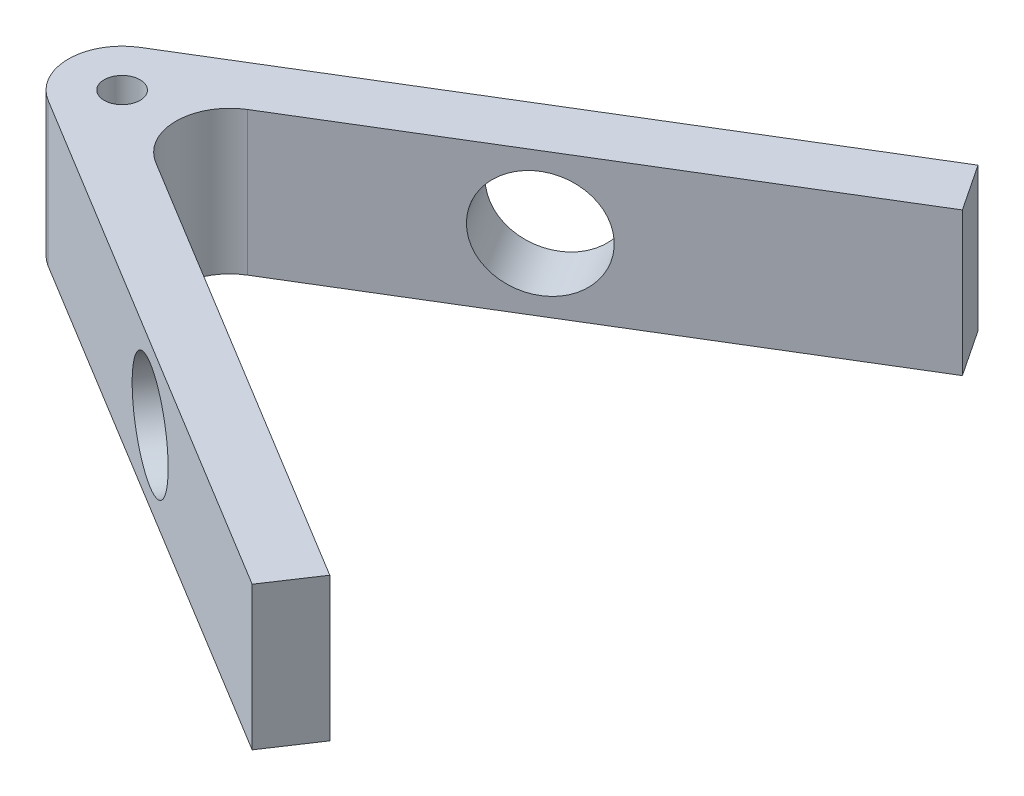
SolidWorks part; units mm, degrees
ref_plane "Front Plane" through (0, 0, 0) normal (0, 0, 1) x (1, 0, 0)
ref_plane "Top Plane" through (0, 0, 0) normal (0, 1, 0) x (1, 0, 0)
ref_plane "Right Plane" through (0, 0, 0) normal (1, 0, 0) x (0, 0, -1)
sketch "Sketch1" plane through (0, 0, 0) normal (0, 1, 0) x (1, 0, 0)
  line L0 (-47.5638, 0) -> (71.5683, 0) construction
  line L1 (-37.328, 12.8145) -> (107.9032, 101.1768)
  line L2 (-7.328, 12.8145) -> (116.5457, 88.1824)
  line L3 (116.5457, 88.1824) -> (107.9032, 101.1768)
  line L4 (116.5457, -88.1824) -> (107.9032, -101.1768)
  line L5 (-7.328, -12.8145) -> (116.5457, -88.1824)
  line L6 (-37.328, -12.8145) -> (107.9032, -101.1768)
  circle A0 centre (-29.5313, 0) radius 5
  arc A1 (-37.328, 12.8145) -> (-37.328, -12.8145) centre (-29.5313, 0) ccw
  arc A2 (-7.328, 12.8145) -> (-7.328, -12.8145) centre (0.4687, 0) ccw
  point P5 (0, 0)
  point P7 (0, 0)
  point P13 (-14.5313, 0)
  point P15 (46.3006, 43.6208)
  point P16 (45.3199, 44.8467)
  point P17 (0, 0)
  point P18 (-28.2254, 15.3288)
  point P19 (0, 0)
  point P20 (-21.0108, 16.5492)
  point P21 (-34.8777, 14.0148)
  point P22 (0, 0)
  point P26 (0, 0)
  dimension "D1" = 10
  dimension "D2" = 15
  dimension "D3" = 15
  dimension "D4" = 15
  dimension "D5" = 170
  dimension "D6" = 145
extrude "Boss-Extrude1" add sketch "Sketch1" along normal blind 40
sketch "Sketch2" plane through (-15.7751, 0, 25.9278) normal (-0.5198, 0, 0.8543) x (0.8543, 0, 0.5198)
  circle A0 centre (59.7713, 20) radius 15
  point P10 (0, 0)
  point P15 (0, 0)
  point P16 (59.7713, 20)
  dimension "D1" = 30
extrude "Cut-Extrude1" cut sketch "Sketch2" against normal blind 40
sketch "Sketch3" plane through (-15.7751, 0, -25.9278) normal (-0.5198, 0, -0.8543) x (-0.8543, 0, 0.5198)
  circle A0 centre (-59.7713, 20) radius 15
  point P4 (-59.7713, 20)
  dimension "D1" = 30
extrude "Cut-Extrude2" cut sketch "Sketch3" against normal blind 40
